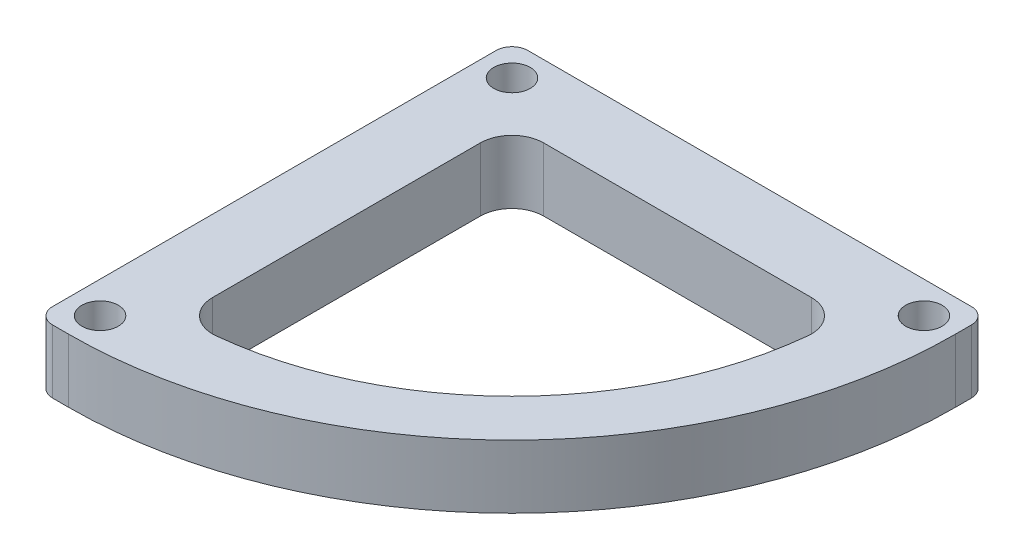
SolidWorks part; units mm, degrees
material "ABS"
ref_plane "前视基准面" through (0, 0, 0) normal (0, 0, 1) x (1, 0, 0)
ref_plane "上视基准面" through (0, 0, 0) normal (0, 1, 0) x (1, 0, 0)
ref_plane "右视基准面" through (0, 0, 0) normal (1, 0, 0) x (0, 0, -1)
sketch "草图1" plane through (0, 0, 0) normal (0, 1, 0) x (1, 0, 0)
  line L1 (-15, 15) -> (15, 15)
  line L2 (-15, 15) -> (-15, -15)
  line L3 (-15, -15) -> (15, -15)
  line L4 (15, 15) -> (15, -15)
  line L5 (0, -15) -> (0, 15) construction
  line L6 (-15, 0) -> (15, 0) construction
  circle A0 centre (13, 13) radius 1.15
  circle A1 centre (13, -13) radius 1.15
  circle A2 centre (-13, -13) radius 1.15
  circle A3 centre (-13, 13) radius 1.15
  point P0 (0, 0)
  dimension "D1" = 26
  dimension "D2" = 26
  dimension "D3" = 2.3
  dimension "D4" = 30
  dimension "D5" = 30
extrude "凸台-拉伸1" add sketch "草图1" along normal blind 4
fillet "圆角1" radius 28 1 edges at (15, 2, 15)
fillet "圆角2" radius 1 3 edges at (-15, 2, -15) (15, 2, -15) (-15, 2, 15)
sketch "草图2" plane through (0, 0, 0) normal (0, 1, 0) x (1, 0, 0)
  line L0 (-13, 13) -> (0, 0) construction
  line L4 (8.4472, 10.4472) -> (-8.4472, 10.4472)
  line L5 (-10.4472, -8.4472) -> (-10.4472, 8.4472)
  line L6 (0, 10.4472) -> (0, -10.5) construction
  line L7 (10.5, 0) -> (-10.4472, 0) construction
  arc A0 (10.4361, 8.2367) -> (-8.2367, -10.4361) centre (-10.4472, 10.4472) cw
  arc A1 (-8.4472, 10.4472) -> (-10.4472, 8.4472) centre (-8.4472, 8.4472) ccw
  arc A2 (-8.2367, -10.4361) -> (-10.4472, -8.4472) centre (-8.4472, -8.4472) cw
  arc A3 (10.4361, 8.2367) -> (8.4472, 10.4472) centre (8.4472, 8.4472) ccw
  point P7 (-10.4472, 10.4472)
  point P13 (10.5528, 10.4472)
  dimension "D2" = 21
  dimension "D3" = 2
  dimension "D1" = 21
extrude "切除-拉伸3" cut sketch "草图2" along normal blind 22
